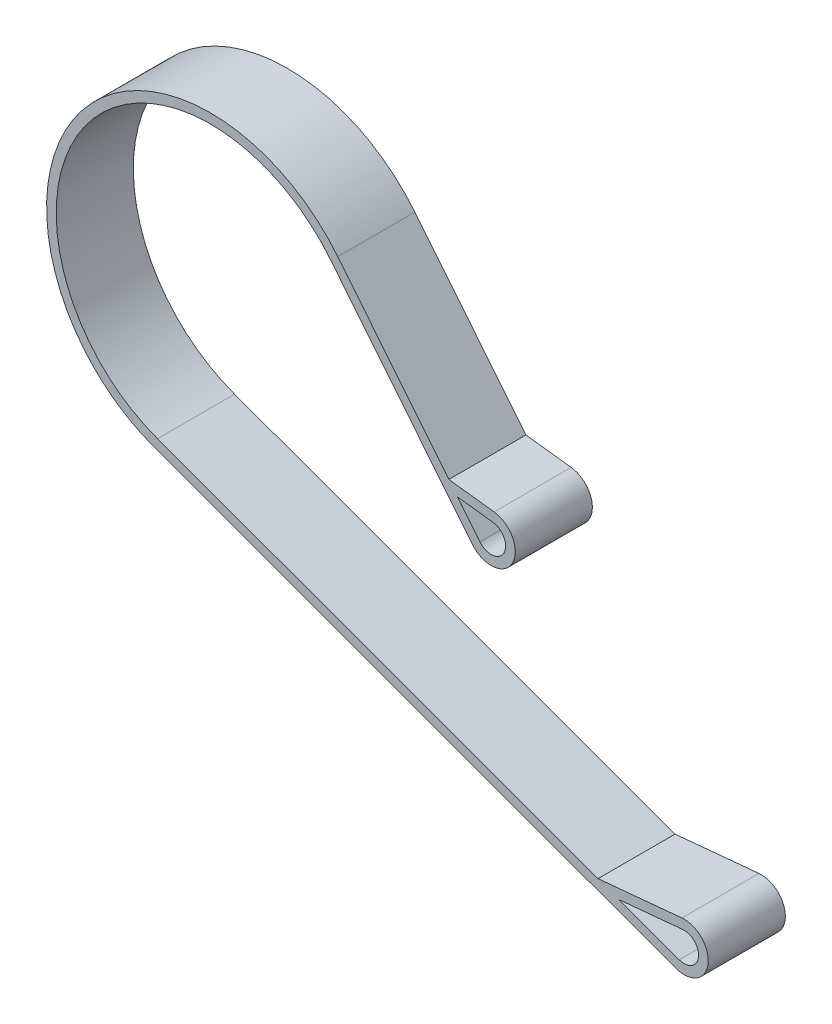
SolidWorks part; units mm, degrees
ref_plane "Front Plane" through (0, 0, 0) normal (0, 0, 1) x (1, 0, 0)
ref_plane "Top Plane" through (0, 0, 0) normal (0, 1, 0) x (1, 0, 0)
ref_plane "Right Plane" through (0, 0, 0) normal (1, 0, 0) x (0, 0, -1)
sketch "Sketch1" plane through (0, 0, 0) normal (0, 0, 1) x (1, 0, 0)
  line L0 (-128.9591, -567.3235) -> (-149.9671, -569.3025) construction
  line L1 (-302.0421, -513.7839) -> (-130.1457, -576.5387) construction
  line L2 (-245.1081, -434.1368) -> (-198.2732, -492.0985) construction
  line L3 (-210.5706, -476.8796) -> (-191.146, -479.2298) construction
  line L4 (-128.9591, -567.3235) -> (-149.9671, -569.3025)
  line L5 (-302.0421, -513.7839) -> (-130.1457, -576.5387)
  line L6 (-245.1081, -434.1368) -> (-198.2732, -492.0985)
  line L7 (-210.5706, -476.8796) -> (-191.146, -479.2298)
  arc A0 (-130.1457, -576.5387) -> (-128.9591, -567.3235) centre (-128.5125, -572.0651) ccw construction
  arc A1 (-245.1081, -434.1368) -> (-302.0421, -513.7839) centre (-284.621, -466.0645) ccw construction
  arc A2 (-198.2732, -492.0985) -> (-191.146, -479.2298) centre (-192.0994, -487.1098) ccw construction
  arc A3 (-130.1457, -576.5387) -> (-128.9591, -567.3235) centre (-128.5125, -572.0651) ccw
  arc A4 (-245.1081, -434.1368) -> (-302.0421, -513.7839) centre (-284.621, -466.0645) ccw
  arc A5 (-198.2732, -492.0985) -> (-191.146, -479.2298) centre (-192.0994, -487.1098) ccw
sketch "Sketch2" plane through (0, 0, 0) normal (0, 0, 1) x (1, 0, 0)
  line L0 (-245.1081, -434.1368) -> (-198.2732, -492.0985) construction
  line L1 (-302.0421, -513.7839) -> (-130.1457, -576.5387) construction
  line L2 (-245.1081, -434.1368) -> (-198.2732, -492.0985)
  line L3 (-302.0421, -513.7839) -> (-130.1457, -576.5387)
  arc A0 (-245.1081, -434.1368) -> (-302.0421, -513.7839) centre (-284.621, -466.0645) ccw construction
  arc A1 (-198.2732, -492.0985) -> (-191.146, -479.2298) centre (-192.0994, -487.1098) ccw construction
  arc A2 (-130.1457, -576.5387) -> (-128.9591, -567.3235) centre (-128.5125, -572.0651) ccw construction
  arc A3 (-245.1081, -434.1368) -> (-302.0421, -513.7839) centre (-284.621, -466.0645) ccw
  arc A4 (-198.2732, -492.0985) -> (-191.146, -479.2298) centre (-192.0994, -487.1098) ccw
  arc A5 (-130.1457, -576.5387) -> (-128.9591, -567.3235) centre (-128.5125, -572.0651) ccw
extrude "Extrude-Thin1" add sketch "Sketch2" along normal blind 25.4 thin thin type one direction wall 3.175
sketch "Sketch3" plane through (-131.2429, 15.879, 0) normal (-0.9928, 0.1201, 0) x (0, 0, 1)
  line L4 (0, -498.7195) -> (0, -501.8945)
  line L5 (0, -501.8945) -> (25.4, -501.8945)
  line L6 (25.4, -501.8945) -> (25.4, -498.7195)
  line L7 (25.4, -498.7195) -> (0, -498.7195)
  line L8 (0, -498.7195) -> (0, -501.8945)
  line L9 (0, -501.8945) -> (25.4, -501.8945)
  line L10 (25.4, -501.8945) -> (25.4, -498.7195)
  line L11 (25.4, -498.7195) -> (0, -498.7195)
  dimension "D1" = 0
extrude "Boss-Extrude1" add sketch "Sketch3" along normal up to next
sketch "Sketch4" plane through (-180.7956, -17.0306, 0) normal (-0.9956, -0.0938, 0) x (0, 0, 1)
  line L4 (0, -549.554) -> (0, -552.729)
  line L5 (0, -552.729) -> (25.4, -552.729)
  line L6 (25.4, -552.729) -> (25.4, -549.554)
  line L7 (25.4, -549.554) -> (0, -549.554)
  line L8 (0, -549.554) -> (0, -552.729)
  line L9 (0, -552.729) -> (25.4, -552.729)
  line L10 (25.4, -552.729) -> (25.4, -549.554)
  line L11 (25.4, -549.554) -> (0, -549.554)
  dimension "D1" = 0
extrude "Boss-Extrude2" add sketch "Sketch4" along normal up to next
